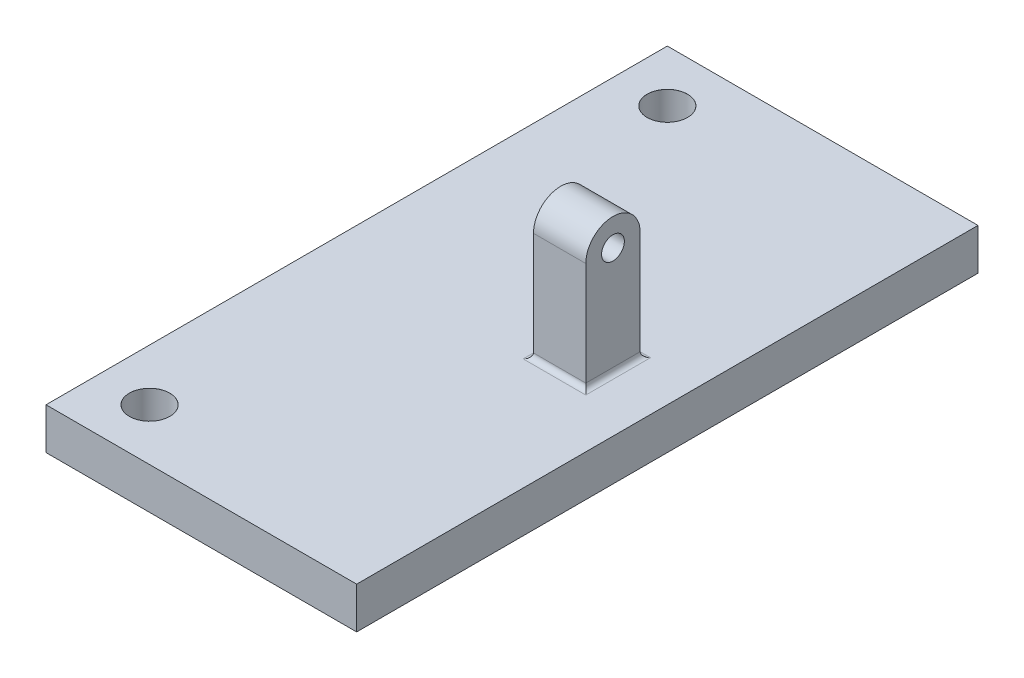
SolidWorks part; units mm, degrees
material "Plain Carbon Steel"
ref_plane "Front Plane" through (0, 0, 0) normal (0, 0, 1) x (1, 0, 0)
ref_plane "Top Plane" through (0, 0, 0) normal (0, 1, 0) x (1, 0, 0)
ref_plane "Right Plane" through (0, 0, 0) normal (1, 0, 0) x (0, 0, -1)
sketch "Sketch1" plane through (0, 0, 0) normal (1, 0, 0) x (0, 0, -1)
  line L1 (-26.25, 0) -> (-26.25, -105)
  line L2 (-26.25, -105) -> (26.25, -105)
  line L3 (26.25, -105) -> (26.25, 0)
  arc A1 (-26.25, 0) -> (26.25, 0) centre (0, 0) cw
extrude "Boss-Extrude1" add sketch "Sketch1" along normal blind 50.5
sketch "Sketch4" plane through (0, 0, 0) normal (-1, 0, 0) x (0, 0, 1)
  point P0 (0, 0)
hole_wizard "Tap Drill for M24x2.0 Tap1" positions "Sketch4" profile "Sketch5" hole size "M24x2.0" standard "ISO" end condition through all
sketch "Sketch5" plane through (0, 0, 0) normal (0, 1, 0) x (0, 0, 1)
  line L0 (0, 0) -> (0, 50.5)
  line L1 (0, 50.5) -> (11, 50.5)
  line L2 (11, 50.5) -> (11, 0.025)
  line L3 (11, 0.025) -> (11.025, 0)
  line L5 (11.025, 0) -> (0, 0)
  line L6 (-11, 0.025) -> (-11.025, 0) construction
  line L11 (0, -6.35) -> (0, 107.95) construction
  dimension "Thru Hole Dia." = 22
  dimension "Thru Hole Depth" = 50.5
  dimension "Near C'Sink Dia." = 22.05
  dimension "Near C'Sink Angle" = 90
sketch "Sketch6" plane through (0, -105, 0) normal (0, -1, 0) x (1, 0, 0)
  line L19 (103, 0) -> (103, 300)
  line L20 (103, 300) -> (-197, 300)
  line L21 (-197, 300) -> (-197, -300)
  line L22 (-197, -300) -> (103, -300)
  line L23 (103, -300) -> (103, 0)
extrude "Boss-Extrude2" add sketch "Sketch6" along normal blind 40
fillet "Fillet1" radius 5 4 edges at (25.25, -105, -26.25) (0, -105, 0) (50.5, -105, 0) (25.25, -105, 26.25)
sketch "Sketch9" plane through (0, -105, 0) normal (0, 1, 0) x (1, 0, 0)
  line L3 (-197, 300) -> (103, 300) construction
  line L4 (-197, -300) -> (-197, 300) construction
  line L5 (103, -300) -> (-197, -300) construction
  point P0 (-147, 250)
  point P2 (-147, -250)
  dimension "D1" = 50
  dimension "D2" = 50
  dimension "D3" = 50
  dimension "D4" = 50
hole_wizard "Tap Drill for M42x3.0 Tap1" positions "Sketch9" profile "Sketch8" hole size "M42x3.0" standard "ISO" end condition through all
sketch "Sketch8" plane through (-147, -105, -250) normal (1, 0, 0) x (0, 0, 1)
  line L0 (0, 0) -> (0, 40)
  line L1 (0, 40) -> (19.5, 40)
  line L2 (19.5, 40) -> (19.5, 0.025)
  line L3 (19.5, 0.025) -> (19.525, 0)
  line L5 (19.525, 0) -> (0, 0)
  line L6 (-19.5, 0.025) -> (-19.525, 0) construction
  line L11 (0, -6.35) -> (0, 107.95) construction
  dimension "Thru Hole Dia." = 39
  dimension "Thru Hole Depth" = 40
  dimension "Near C'Sink Dia." = 39.05
  dimension "Near C'Sink Angle" = 90
